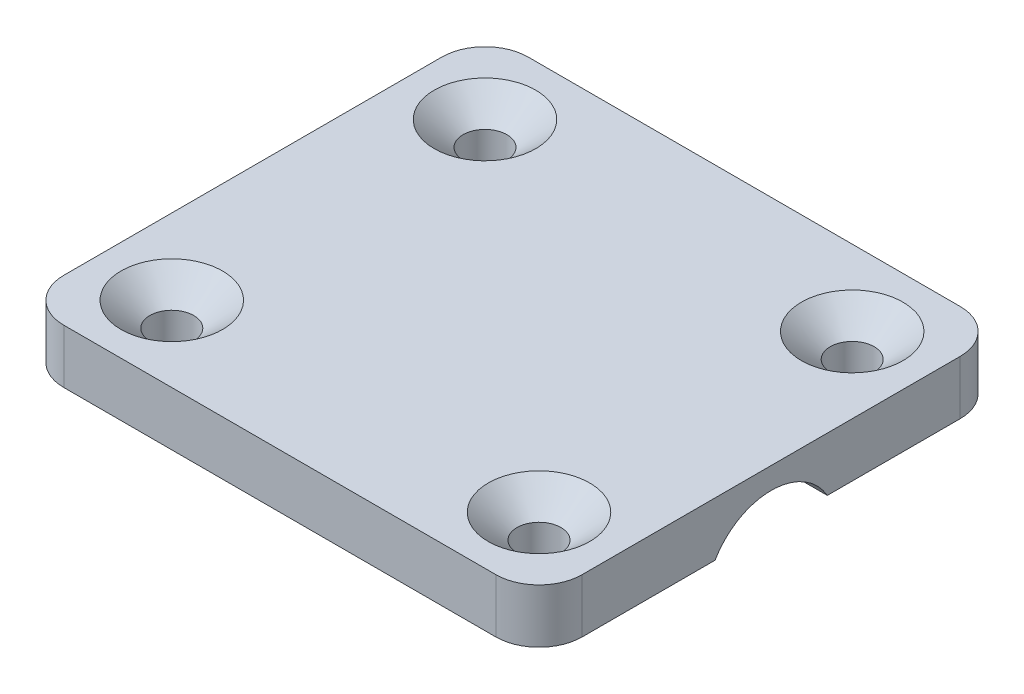
SolidWorks part; units mm, degrees
ref_plane "Front Plane" through (0, 0, 0) normal (0, 0, 1) x (1, 0, 0)
ref_plane "Top Plane" through (0, 0, 0) normal (0, 1, 0) x (1, 0, 0)
ref_plane "Right Plane" through (0, 0, 0) normal (1, 0, 0) x (0, 0, -1)
sketch "Sketch1" plane through (0, 0, 0) normal (0, 1, 0) x (1, 0, 0)
  line L1 (-24, 21.5) -> (24, 21.5)
  line L2 (-24, 21.5) -> (-24, -21.5)
  line L3 (-24, -21.5) -> (24, -21.5)
  line L4 (24, 21.5) -> (24, -21.5)
  line L5 (-24, 21.5) -> (24, -21.5) construction
  line L6 (-24, -21.5) -> (24, 21.5) construction
  point P0 (0, 0)
  dimension "D1" = 48
  dimension "D2" = 43
extrude "Boss-Extrude1" add sketch "Sketch1" along normal blind 5
fillet "Fillet1" radius 4 4 edges at (-24, 2.5, 21.5) (-24, 2.5, -21.5) (24, 2.5, -21.5) (24, 2.5, 21.5)
hole_wizard "CSK for 1/4 Flat Head Machine Screw (100)1" positions "Sketch2" profile "Sketch3" countersink size "1/4" standard "ANSI Inch"
sketch "Sketch2" plane through (0, 5, 0) normal (0, 1, 0) x (1, 0, 0)
  line L0 (24, -17.5) -> (24, 17.5) construction
  line L1 (-20, -21.5) -> (20, -21.5) construction
  line L2 (20, 21.5) -> (-20, 21.5) construction
  point P0 (17, -14.5)
  point P2 (17, 14.5)
  dimension "D1" = 7
  dimension "D2" = 7
  dimension "D3" = 7
  dimension "D4" = 7
sketch "Sketch3" plane through (17, 5, 14.5) normal (1, 0, 0) x (0, 0, 1)
  line L0 (0, 0) -> (0, 30)
  line L1 (0, 30) -> (2.032, 28.7791)
  line L2 (2.032, 28.7791) -> (2.032, 2.2379)
  line L3 (2.032, 2.2379) -> (4.699, 0)
  line L5 (4.699, 0) -> (0, 0)
  line L6 (-2.032, 2.2379) -> (-4.699, 0) construction
  line L10 (0, 30) -> (-2.032, 28.7791) construction
  line L11 (0, -6.35) -> (0, 107.95) construction
  dimension "Hole Dia." = 4.064
  dimension "Hole Depth" = 30
  dimension "Near C'Sink Dia." = 9.398
  dimension "Near C'Sink Angle" = 100
  dimension "Drill Angle" = 118
mirror "Mirror1" about plane through (0, 0, 0) normal (1, 0, 0) of "CSK for 1/4 Flat Head Machine Screw (100)1"
sketch "Sketch6" plane through (24, 0, 0) normal (1, 0, 0) x (0, 0, -1)
  line L0 (-5.1962, 0) -> (5.1962, 0)
  line L1 (-17.5, 0) -> (17.5, 0) construction
  line L2 (0, 55) -> (0, -55) construction
  line L3 (-17.5, 5) -> (17.5, 5) construction
  arc A0 (-5.1962, 0) -> (5.1962, 0) centre (0, -3) cw
  point P5 (0, 0)
  dimension "D1" = 6
  dimension "D2" = 8
extrude "Cut-Extrude2" cut sketch "Sketch6" against normal blind 55
